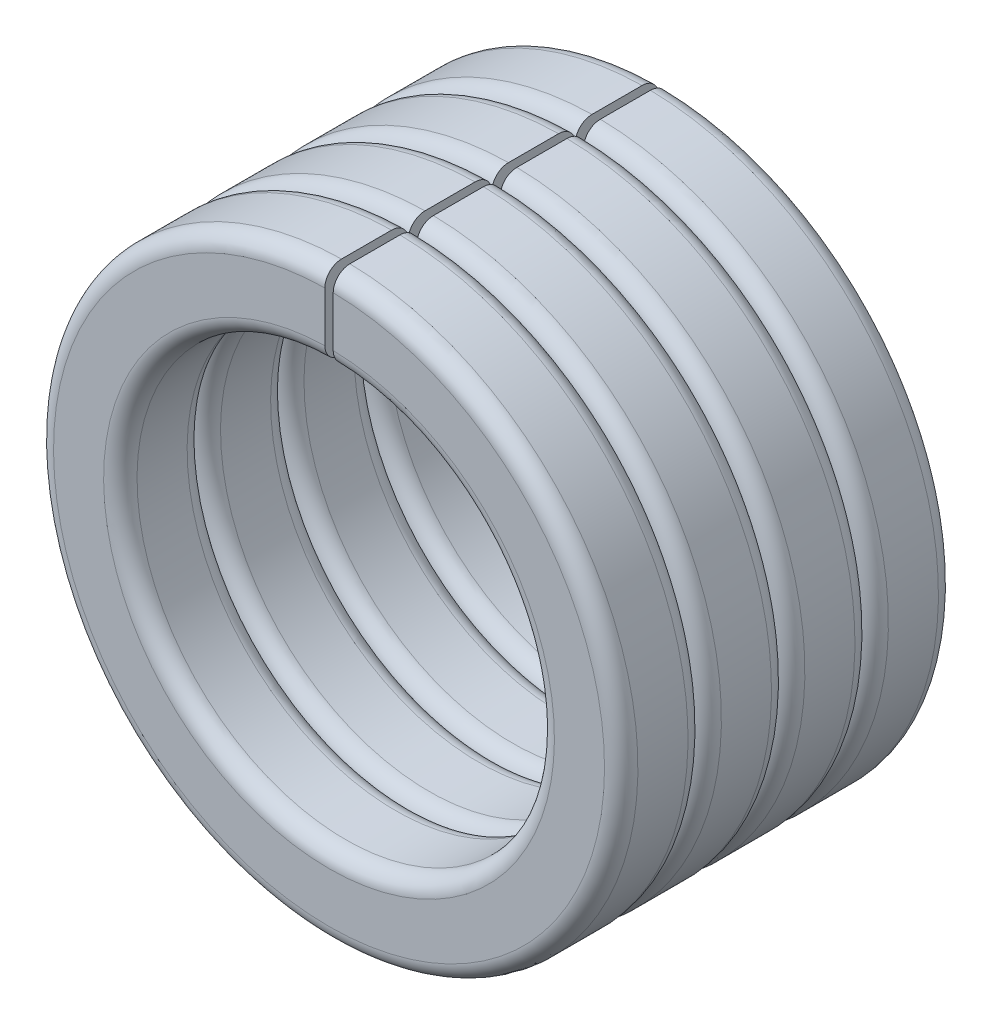
SolidWorks part; units mm, degrees
material "VITON"
ref_plane "Front Plane" through (0, 0, 0) normal (0, 0, 1) x (1, 0, 0)
ref_plane "Top Plane" through (0, 0, 0) normal (0, 1, 0) x (1, 0, 0)
ref_plane "Right Plane" through (0, 0, 0) normal (1, 0, 0) x (0, 0, -1)
sketch "Sketch2" plane through (0, 0, 0) normal (0, 1, 0) x (1, 0, 0)
  line L0 (0, 0) -> (0, 55.4551) construction
  line L1 (-27, 5.7) -> (-33, 5.7)
  line L2 (-25, 7.7) -> (-25, 13.7)
  line L3 (-27, 15.7) -> (-33, 15.7)
  line L4 (-35, 7.7) -> (-35, 13.7)
  line L5 (-25, 5.7) -> (-35, 15.7) construction
  line L6 (-25, 15.7) -> (-35, 5.7) construction
  arc A0 (-25, 13.7) -> (-27, 15.7) centre (-27, 13.7) ccw
  arc A1 (-27, 5.7) -> (-25, 7.7) centre (-27, 7.7) ccw
  arc A2 (-33, 5.7) -> (-35, 7.7) centre (-33, 7.7) cw
  arc A3 (-33, 15.7) -> (-35, 13.7) centre (-33, 13.7) ccw
  point P0 (-30, 10.7)
  dimension "D4" = 2
  dimension "D1" = 10
  dimension "D2" = 10
  dimension "D3" = 25
revolve "Revolve1" add sketch "Sketch2" angle 360 about L0
sketch "Sketch3" plane through (0, 0, -5.7) normal (0, 0, 1) x (1, 0, 0)
  line L1 (0.5, -0.9445) -> (-0.5, -0.9445)
  line L2 (0.5, -0.9445) -> (0.5, 75.1933)
  line L3 (0.5, 75.1933) -> (-0.5, 75.1933)
  line L4 (-0.5, -0.9445) -> (-0.5, 75.1933)
  line L5 (0.5, -0.9445) -> (-0.5, 75.1933) construction
  line L6 (0.5, 75.1933) -> (-0.5, -0.9445) construction
  point P0 (0, 37.1244)
  dimension "D1" = 1
extrude "Cut-Extrude1" cut sketch "Sketch3" against normal blind 20
pattern_linear "LPattern1" count 4 spacing 10 along (0, 0, -1) of "Revolve1", "Cut-Extrude1"
